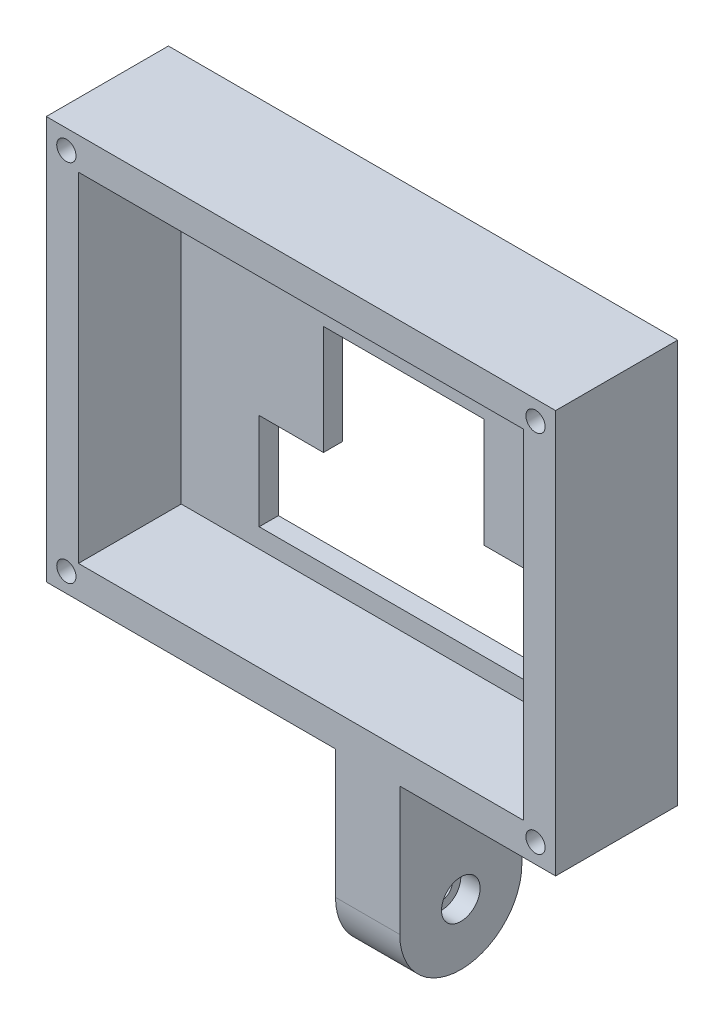
SolidWorks part; units mm, degrees
ref_plane "前视基准面" through (0, 0, 0) normal (0, 0, 1) x (1, 0, 0)
ref_plane "上视基准面" through (0, 0, 0) normal (0, 1, 0) x (1, 0, 0)
ref_plane "右视基准面" through (0, 0, 0) normal (1, 0, 0) x (0, 0, -1)
other "Configuration Table"
sketch "草图1" plane through (0, 0, 0) normal (0, 0, 1) x (1, 0, 0)
  line L5 (39.625, 0) -> (-39.625, 0)
  line L6 (39.625, 0) -> (39.625, 62.72)
  line L7 (39.625, 62.72) -> (-39.625, 62.72)
  line L8 (-39.625, 0) -> (-39.625, 62.72)
  point P5 (0, 0)
  dimension "D1" = 79.25
  dimension "D2" = 62.72
extrude "凸台-拉伸1" add sketch "草图1" along normal blind 19
sketch "草图2" plane through (0, 0, 19) normal (0, 0, 1) x (1, 0, 0)
  line L0 (0, 0) -> (0, 21.6302) construction
  line L1 (-34.625, 57.72) -> (34.625, 57.72)
  line L2 (-34.625, 57.72) -> (-34.625, 5)
  line L3 (-34.625, 5) -> (34.625, 5)
  line L4 (34.625, 57.72) -> (34.625, 5)
  line L5 (39.625, 0) -> (39.625, 62.72) construction
  line L6 (-39.625, 0) -> (39.625, 0) construction
  line L7 (39.625, 62.72) -> (-39.625, 62.72) construction
  point P7 (0, 5)
  dimension "D1" = 5
  dimension "D2" = 5
  dimension "D3" = 5
extrude "切除-拉伸1" cut sketch "草图2" against normal blind 16
sketch "草图3" plane through (0, 0, 0) normal (0, 0, -1) x (-1, 0, 0)
  line L0 (0, 0) -> (0, 52.6984) construction
  line L1 (39.625, 0) -> (-39.625, 0) construction
  line L2 (12.5, 40) -> (-12.5, 40)
  line L3 (-12.5, 40) -> (-12.5, 23)
  line L4 (-12.5, 23) -> (-22.5, 23)
  line L5 (-22.5, 23) -> (-22.5, 8)
  line L6 (-22.5, 8) -> (22.5, 8)
  line L7 (22.5, 23) -> (22.5, 8)
  line L8 (12.5, 23) -> (22.5, 23)
  line L9 (12.5, 40) -> (12.5, 23)
  point P4 (0, 52.6984)
  point P11 (0, 8)
  point P14 (0, 40)
  dimension "D1" = 45
  dimension "D2" = 25
  dimension "D3" = 40
  dimension "D4" = 8
  dimension "D5" = 15
extrude "切除-拉伸2" cut sketch "草图3" against normal blind 10
sketch "草图4" plane through (0, 0, 0) normal (0, 0, -1) x (-1, 0, 0)
  line L0 (0, 0) -> (0, 66.3388) construction
  line L1 (39.625, 0) -> (-39.625, 0) construction
  line L2 (-39.625, 62.72) -> (39.625, 62.72) construction
  line L3 (-39.625, 31.36) -> (50.2458, 31.36) construction
  line L4 (-39.625, 0) -> (-39.625, 62.72) construction
  circle A0 centre (-36.5, 59.72) radius 1.5
  circle A1 centre (36.5, 59.72) radius 1.5
  circle A2 centre (-36.5, 3) radius 1.5
  circle A3 centre (36.5, 3) radius 1.5
  dimension "D3" = 3
  dimension "D1" = 73
  dimension "D2" = 3
extrude "切除-拉伸3" cut sketch "草图4" against normal through all and the other way through all
sketch "草图5" plane through (-39.625, 0, 0) normal (-1, 0, 0) x (0, 0, 1)
  line L0 (0, 0) -> (0, -20)
  line L1 (19, 0) -> (19, -20)
  line L2 (0, 0) -> (19, 0)
  arc A0 (0, -20) -> (19, -20) centre (9.5, -20) ccw
  circle A1 centre (9.5, -20) radius 1.7
  dimension "D1" = 20
  dimension "D2" = 3.4
extrude "凸台-拉伸2" add sketch "草图5" along normal blind 10 from offset 55 offset against normal yes
sketch "草图6" plane through (15.375, 0, 0) normal (1, 0, 0) x (0, 0, -1)
  circle A0 centre (-9.5, -20) radius 3
  dimension "D1" = 6
extrude "切除-拉伸4" cut sketch "草图6" against normal blind 3
